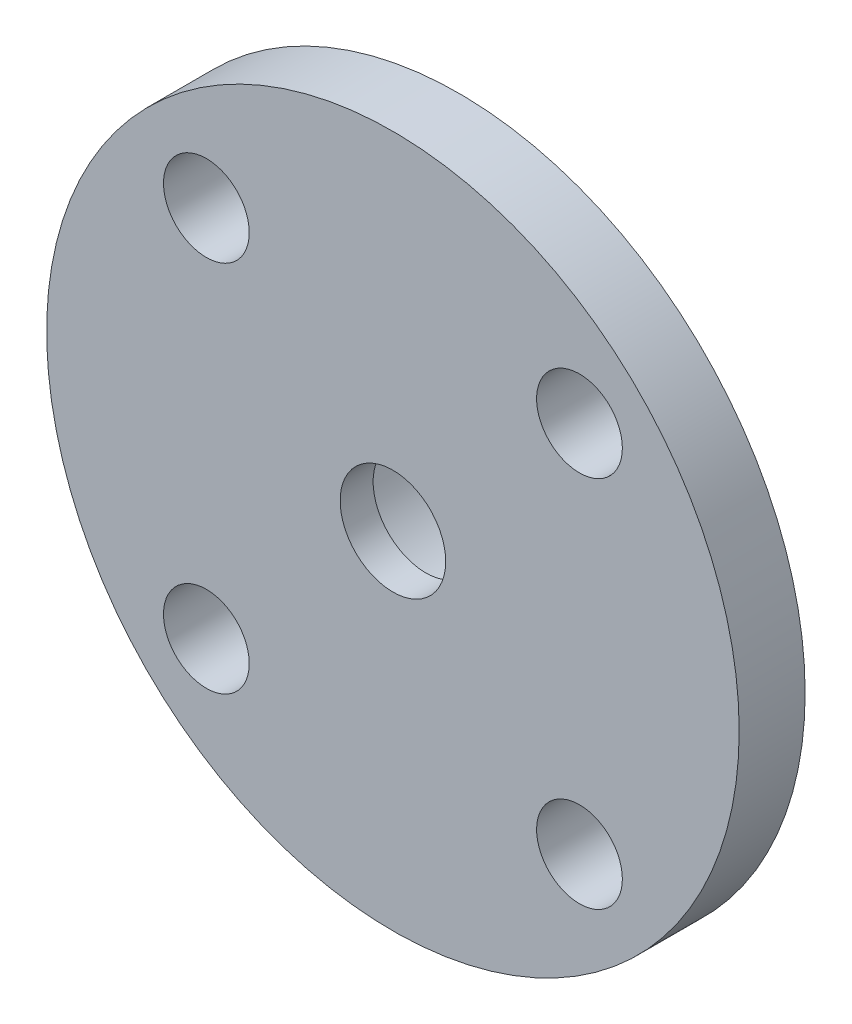
SolidWorks part; units mm, degrees
ref_plane "Спереди" through (0, 0, 0) normal (0, 0, 1) x (1, 0, 0)
ref_plane "Сверху" through (0, 0, 0) normal (0, 1, 0) x (1, 0, 0)
ref_plane "Справа" through (0, 0, 0) normal (1, 0, 0) x (0, 0, -1)
sketch "Эскиз1" plane through (0, 0, 0) normal (0, 1, 0) x (1, 0, 0)
  line L0 (-3.2, 0) -> (-21, 0)
  line L1 (-21, 0) -> (-21, 4)
  line L2 (-21, 4) -> (-9.5, 4)
  line L3 (-9.5, 4) -> (-9.5, 7.8)
  line L4 (-9.5, 7.8) -> (-6, 7.8)
  line L5 (-6, 7.8) -> (-6, 2)
  line L6 (-6, 2) -> (-3.2, 2)
  line L7 (-3.2, 2) -> (-3.2, 0)
  line L8 (0, 0) -> (0, 11778.0468) construction
  dimension "D1" = 3.2
  dimension "D2" = 6
  dimension "D3" = 9.5
  dimension "D4" = 21
  dimension "D5" = 4
  dimension "D6" = 2
  dimension "D7" = 5.8
revolve "Повернуть1" add sketch "Эскиз1" angle 360 about L8
sketch "Эскиз2" plane through (0, 0, 0) normal (0, 0, 1) x (1, 0, 0)
  line L0 (0, 0) -> (0, 21) construction
  circle A0 centre (11.3137, 11.3137) radius 2.6
  circle A1 centre (0, 0) radius 21 construction
  dimension "D1" = 5.2
  dimension "D2" = 16
  dimension "D3" = 45
extrude "Вырез-Вытянуть1" cut sketch "Эскиз2" against normal up to surface (4 mm away) up to face at (21, 0, -4)
pattern_circular "Круговой массив1" count 4 over 360 about axis through (0, 0, 0) along (0, 0, 1) of "Вырез-Вытянуть1"
